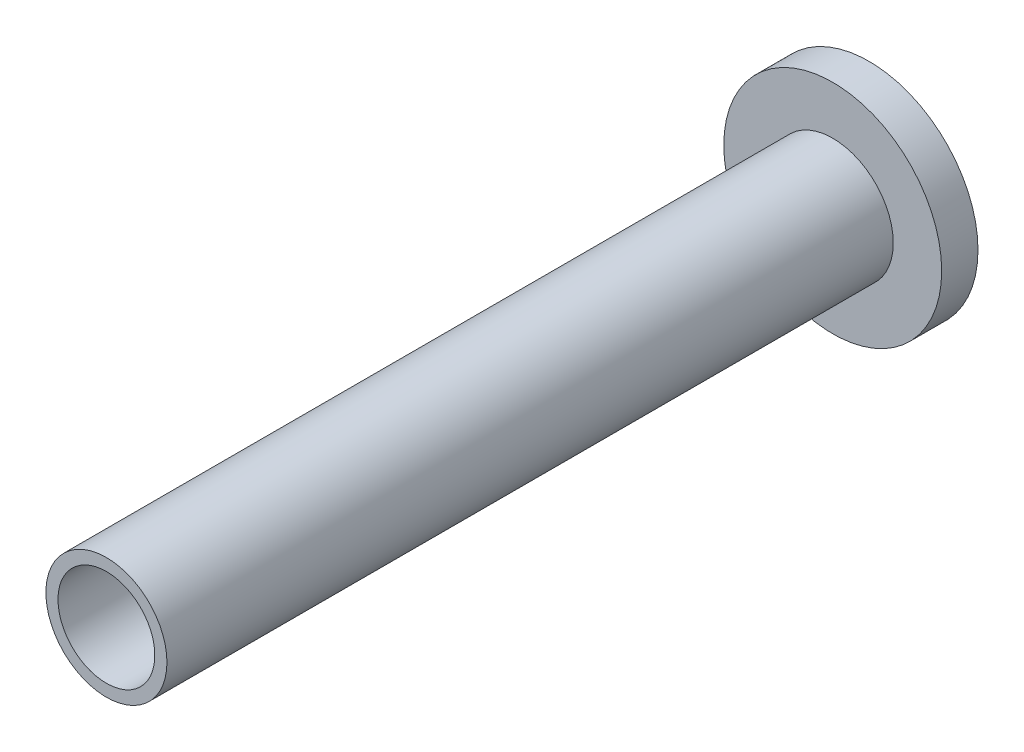
SolidWorks part; units mm, degrees
ref_plane "Plan de face" through (0, 0, 0) normal (0, 0, 1) x (1, 0, 0)
ref_plane "Plan de dessus" through (0, 0, 0) normal (0, 1, 0) x (1, 0, 0)
ref_plane "Plan de droite" through (0, 0, 0) normal (1, 0, 0) x (0, 0, -1)
sketch "Esquisse1" plane through (0, 0, 0) normal (0, 0, 1) x (1, 0, 0)
  circle A0 centre (0, 0) radius 2.5
  dimension "D1" = 5
extrude "Boss.-Extru.1" add sketch "Esquisse1" along normal blind 30
sketch "Esquisse2" plane through (0, 0, 0) normal (0, 0, 1) x (1, 0, 0)
  line L1 (-1.7187, 0.1158) -> (1.7187, 0.1158)
  line L2 (-1.7187, 0.1158) -> (-1.7187, -0.1158)
  line L3 (-1.7187, -0.1158) -> (1.7187, -0.1158)
  line L4 (1.7187, 0.1158) -> (1.7187, -0.1158)
  line L5 (-1.7187, 0.1158) -> (1.7187, -0.1158) construction
  line L6 (-1.7187, -0.1158) -> (1.7187, 0.1158) construction
  line L7 (-0.1158, -1.7187) -> (0.1158, -1.7187)
  line L8 (-0.1158, -1.7187) -> (-0.1158, 1.7187)
  line L9 (-0.1158, 1.7187) -> (0.1158, 1.7187)
  line L10 (0.1158, -1.7187) -> (0.1158, 1.7187)
  line L11 (-0.1158, -1.7187) -> (0.1158, 1.7187) construction
  line L12 (-0.1158, 1.7187) -> (0.1158, -1.7187) construction
  circle A0 centre (0, 0) radius 4.5
  dimension "D1" = 9
extrude "Boss.-Extru.2" add sketch "Esquisse2" against normal blind 1.5 contours A0 L10 L7 L8 L3 L2 L1 L9 L4
sketch "Esquisse3" plane through (0, 0, 30) normal (0, 0, 1) x (1, 0, 0)
  circle A0 centre (0, 0) radius 2
  dimension "D1" = 4
extrude "Enlèv. mat.-Extru.1" cut sketch "Esquisse3" against normal blind 10 and the other way through all
cosmetic thread "Représentation de filetage1" parameters "D2"=5
